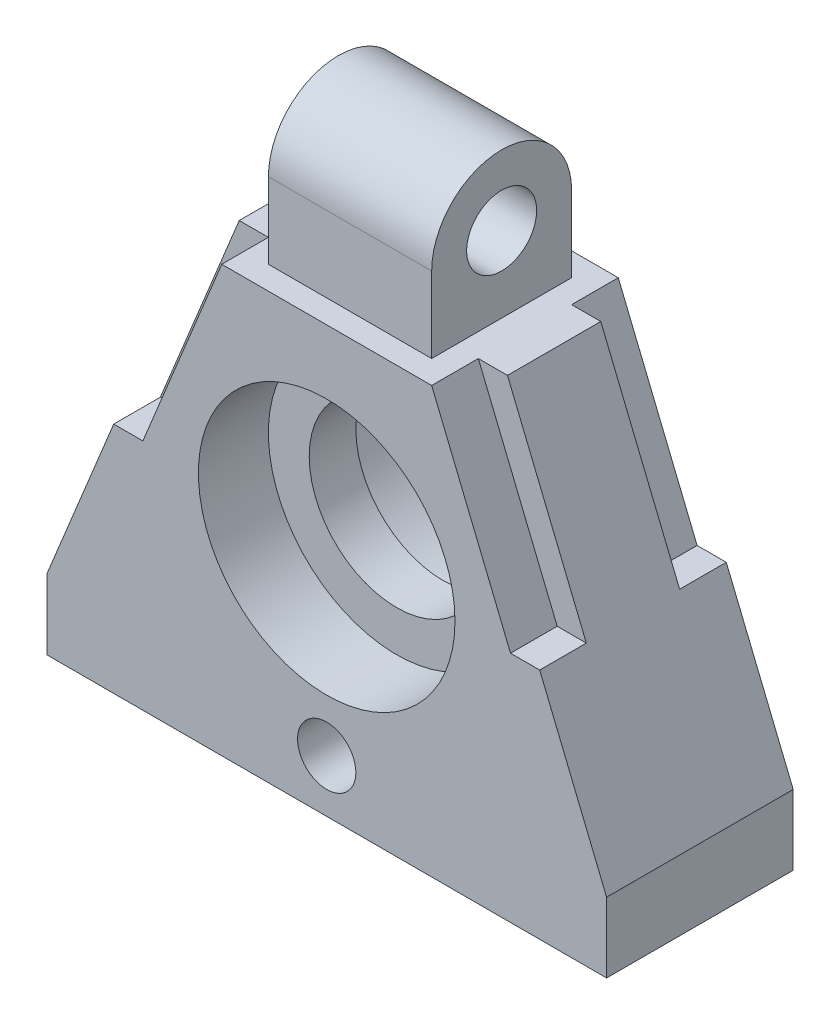
SolidWorks part; units mm, degrees
ref_plane "Alzado" through (0, 0, 0) normal (0, 0, 1) x (1, 0, 0)
ref_plane "Planta" through (0, 0, 0) normal (0, 1, 0) x (1, 0, 0)
ref_plane "Vista lateral" through (0, 0, 0) normal (1, 0, 0) x (0, 0, -1)
sketch "Croquis1" plane through (0, 0, 0) normal (0, 0, 1) x (1, 0, 0)
  line L0 (-23, 73) -> (23, 73)
  line L1 (23, 73) -> (48, 12)
  line L2 (48, 12) -> (48, 0)
  line L3 (48, 0) -> (-48, 0)
  line L4 (-48, 0) -> (-48, 12)
  line L5 (-48, 12) -> (-23, 73)
  circle A0 centre (0, 40) radius 15
  circle A1 centre (0, 9) radius 5
  point P3 (0, 73)
  point P7 (0, 0)
  point P13 (-2.4993, 26.4017)
  point P14 (0, 0)
  point P15 (0, 0)
  dimension "D5" = 10
  dimension "D6" = 30
  dimension "D1" = 73
  dimension "D2" = 46
  dimension "D3" = 96
  dimension "D4" = 12
  dimension "D7" = 9
  dimension "D8" = 33
extrude "Saliente-Extruir1" add sketch "Croquis1" along normal mid plane 32
sketch "Croquis2" plane through (0, 0, 16) normal (0, 0, 1) x (1, 0, 0)
  circle A1 centre (0, 40) radius 22
  circle A2 centre (0, 40) radius 15
  circle A3 centre (0, 40) radius 15 construction
  dimension "D1" = 44
extrude "Cortar-Extruir1" cut sketch "Croquis2" against normal blind 12
sketch "Croquis3" plane through (0, 0, 16) normal (0, 0, 1) x (1, 0, 0)
  line L0 (0, 62) -> (0, 18) construction
  line L1 (23, 73) -> (36.5246, 40)
  line L2 (48, 12) -> (23, 73) construction
  line L3 (36.5246, 40) -> (31.5246, 40)
  line L4 (31.5246, 40) -> (18, 73)
  line L5 (23, 73) -> (-23, 73) construction
  line L6 (18, 73) -> (23, 73)
  line L7 (-18, 73) -> (-23, 73)
  line L8 (-31.5246, 40) -> (-18, 73)
  line L9 (-36.5246, 40) -> (-31.5246, 40)
  line L10 (-23, 73) -> (-36.5246, 40)
  circle A0 centre (0, 40) radius 22 construction
  circle A1 centre (0, 40) radius 22 construction
  point P16 (0, 40)
  dimension "D1" = 5
extrude "Cortar-Extruir2" cut sketch "Croquis3" against normal blind 8
mirror "Simetría1" about plane through (0, 0, 0) normal (0, 0, 1) of "Cortar-Extruir2", "Cortar-Extruir1"
sketch "Croquis4" plane through (0, 0, 0) normal (1, 0, 0) x (0, 0, -1)
  line L0 (-12, 73) -> (12, 73)
  line L1 (12, 73) -> (12, 86)
  line L2 (-12, 86) -> (-12, 73)
  line L3 (-8, 73) -> (8, 73) construction
  arc A0 (12, 86) -> (-12, 86) centre (0, 86) ccw
  circle A1 centre (0, 86) radius 6
  point P5 (0, 0)
  dimension "D1" = 12
  dimension "D2" = 12
  dimension "D3" = 86
extrude "Saliente-Extruir2" add sketch "Croquis4" along normal mid plane 28
